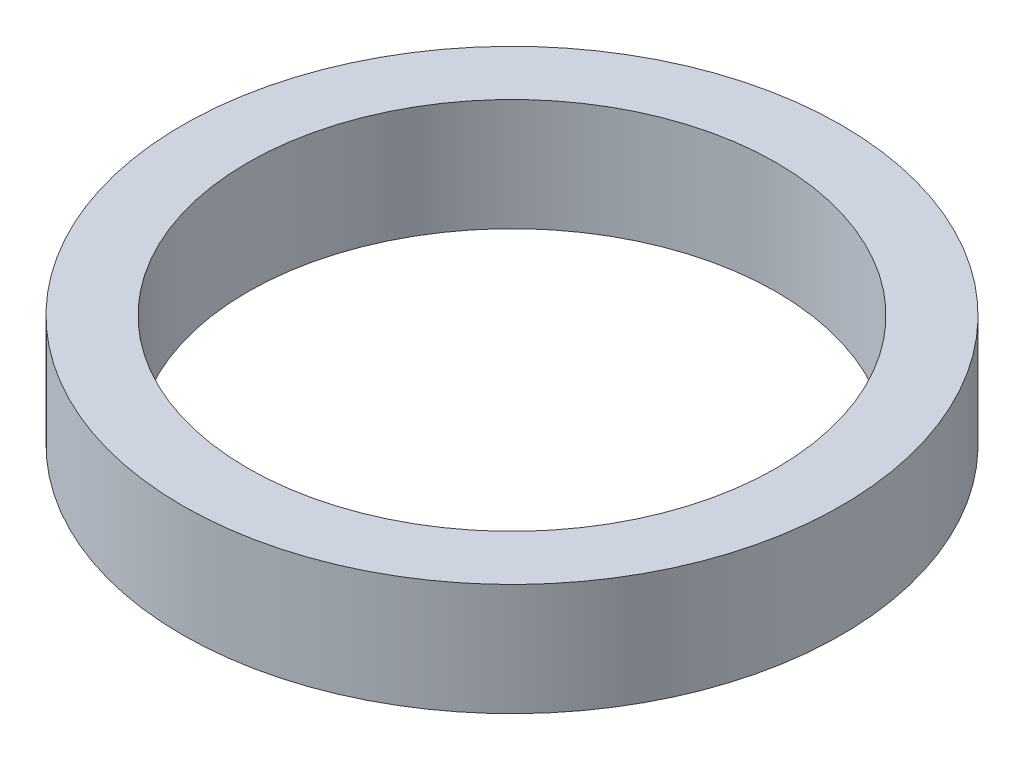
SolidWorks part; units mm, degrees
ref_plane "Front Plane" through (0, 0, 0) normal (0, 0, 1) x (1, 0, 0)
ref_plane "Top Plane" through (0, 0, 0) normal (0, 1, 0) x (1, 0, 0)
ref_plane "Right Plane" through (0, 0, 0) normal (1, 0, 0) x (0, 0, -1)
sketch "Sketch1" plane through (0, 0, 0) normal (0, 1, 0) x (1, 0, 0)
  circle A0 centre (0, 0) radius 16.2
  circle A1 centre (0, 0) radius 13
  dimension "D1" = 3.2
  dimension "D2" = 26
extrude "Boss-Extrude1" add sketch "Sketch1" along normal blind 5.5
